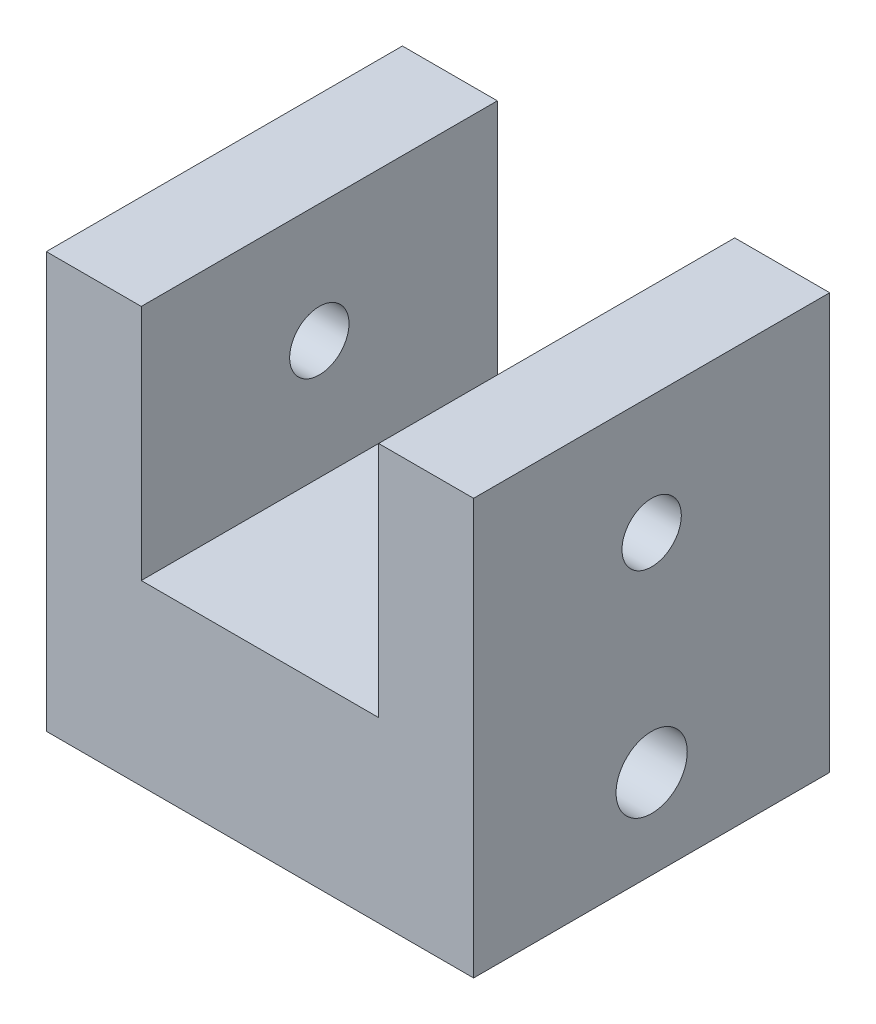
SolidWorks part; units mm, degrees
ref_plane "Płaszczyzna przednia" through (0, 0, 0) normal (0, 0, 1) x (1, 0, 0)
ref_plane "Płaszczyzna górna" through (0, 0, 0) normal (0, 1, 0) x (1, 0, 0)
ref_plane "Płaszczyzna prawa" through (0, 0, 0) normal (1, 0, 0) x (0, 0, -1)
sketch "Szkic1" plane through (0, 0, 0) normal (0, 0, 1) x (1, 0, 0)
  line L0 (-8, 20) -> (-8, -15)
  line L1 (0, 0) -> (20, 0)
  line L2 (0, 0) -> (0, 20)
  line L5 (-8, 20) -> (0, 20)
  line L6 (-8, -15) -> (28, -15)
  line L8 (20, 0) -> (20, 20)
  line L9 (20, 20) -> (28, 20)
  line L10 (28, 20) -> (28, -15)
  point P10 (0, 0)
  dimension "D1" = 20
  dimension "D2" = 20
  dimension "D3" = 8
  dimension "D4" = 35
  dimension "D5" = 8
extrude "Dodanie-wyciągnięcie1" add sketch "Szkic1" along normal blind 30
sketch "Szkic2" plane through (28, 0, 0) normal (1, 0, 0) x (0, 0, -1)
  line L0 (0, -15) -> (0, 20) construction
  line L1 (-30, -15) -> (0, -15) construction
  line L2 (-30, 20) -> (0, 20) construction
  circle A0 centre (-15, -7.5) radius 3
  circle A1 centre (-15, 10) radius 2.5
  dimension "D2" = 6
  dimension "D3" = 7.5
  dimension "D4" = 5
  dimension "D6" = 10
  dimension "D1" = 15
  dimension "D5" = 15
extrude "Wytnij-wyciągnięcie1" cut sketch "Szkic2" against normal through all
